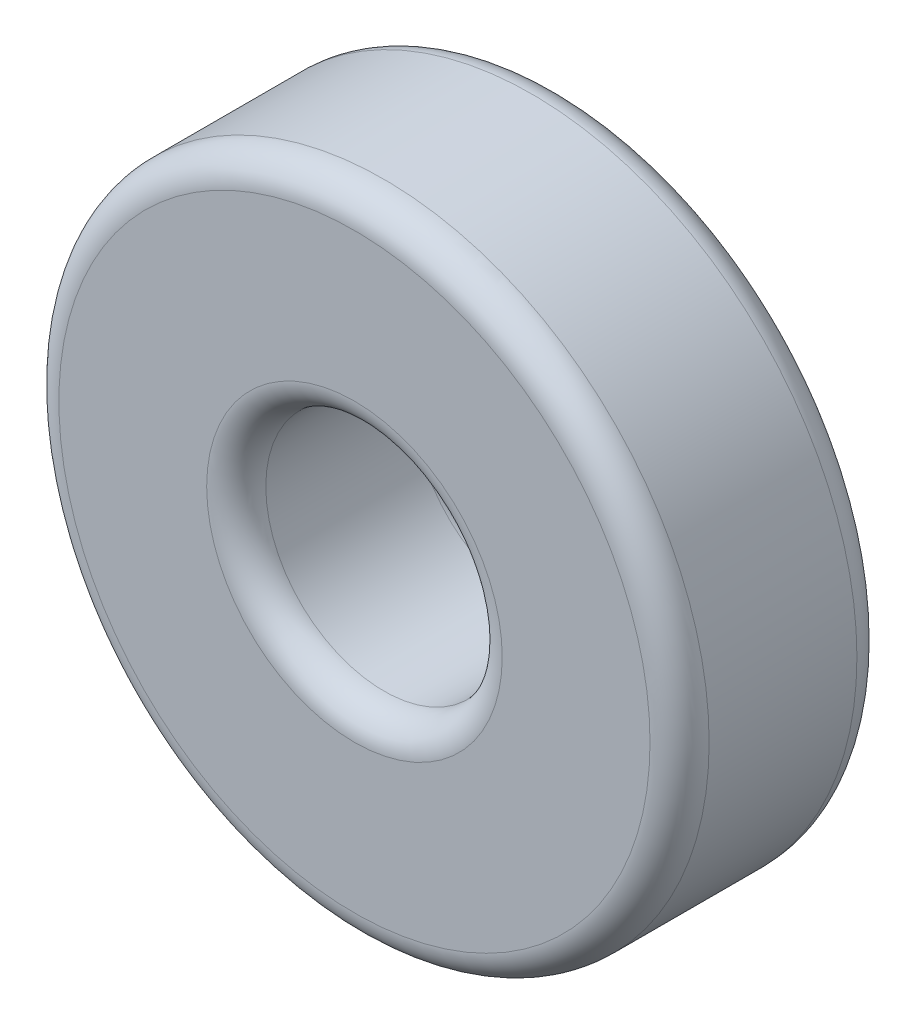
SolidWorks part; units mm, degrees
ref_plane "Plan de face" through (0, 0, 0) normal (1, 0, 0) x (0, 1, 0)
ref_plane "Plan de dessus" through (0, 0, 0) normal (0, 0, 1) x (0, 1, 0)
ref_plane "Plan de droite" through (0, 0, 0) normal (0, 1, 0) x (-1, 0, 0)
sketch "Esquisse1" plane through (0, 0, 0) normal (0, 0, 1) x (0, 1, 0)
  circle A0 centre (0, 0) radius 4
  circle A1 centre (0, 0) radius 11
  dimension "D1" = 22
  dimension "D2" = 8
extrude "Boss.-Extru.1" add sketch "Esquisse1" along normal blind 7
fillet "Congé1" radius 1 4 edges at (4, 0, 0) (4, 0, 7) (11, 0, 0) (11, 0, 7)
